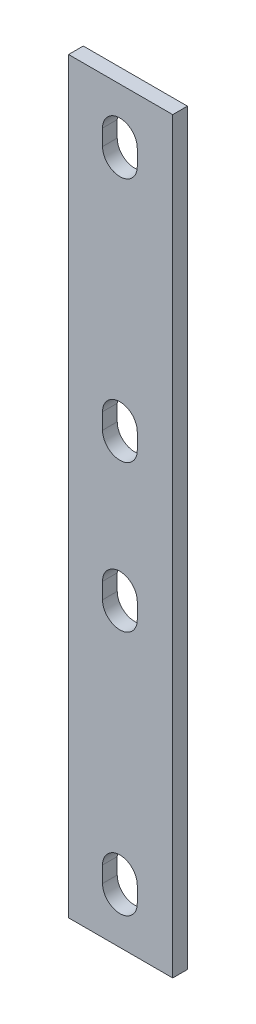
SolidWorks part; units mm, degrees
ref_plane "Front Plane" through (0, 0, 0) normal (0, 0, 1) x (1, 0, 0)
ref_plane "Top Plane" through (0, 0, 0) normal (0, 1, 0) x (1, 0, 0)
ref_plane "Right Plane" through (0, 0, 0) normal (1, 0, 0) x (0, 0, -1)
sketch "Sketch1" plane through (0, 0, 0) normal (0, 0, 1) x (1, 0, 0)
  line L1 (0, 0) -> (39, 0)
  line L2 (0, 0) -> (0, -280)
  line L3 (0, -280) -> (39, -280)
  line L4 (39, 0) -> (39, -280)
  dimension "D1" = 280
  dimension "D2" = 39
extrude "Boss-Extrude1" add sketch "Sketch1" along normal blind 5.5
sketch "Sketch4" plane through (0, 0, 5.5) normal (0, 0, 1) x (1, 0, 0)
  line L0 (0, -140) -> (21.8594, -140) construction
  line L5 (0, 0) -> (0, -280) construction
  line L6 (19.2173, -170.5) -> (19.2173, -164.5) construction
  line L7 (25.7173, -170.5) -> (25.7173, -164.5)
  line L8 (19.2173, -109.5) -> (19.2173, -115.5) construction
  line L9 (25.7173, -109.5) -> (25.7173, -115.5)
  line L10 (12.7173, -109.5) -> (12.7173, -115.5)
  line L11 (19.2173, -23.5) -> (19.2173, -17.5) construction
  line L12 (25.7173, -23.5) -> (25.7173, -17.5)
  line L13 (12.7173, -23.5) -> (12.7173, -17.5)
  line L14 (12.7173, -170.5) -> (12.7173, -164.5)
  line L15 (19.2173, -256.5) -> (19.2173, -262.5) construction
  line L16 (25.7173, -256.5) -> (25.7173, -262.5)
  line L17 (12.7173, -256.5) -> (12.7173, -262.5)
  arc A0 (25.7173, -109.5) -> (12.7173, -109.5) centre (19.2173, -109.5) ccw
  arc A1 (12.7173, -115.5) -> (25.7173, -115.5) centre (19.2173, -115.5) ccw
  arc A2 (25.7173, -23.5) -> (12.7173, -23.5) centre (19.2173, -23.5) cw
  arc A3 (12.7173, -17.5) -> (25.7173, -17.5) centre (19.2173, -17.5) cw
  arc A4 (25.7173, -170.5) -> (12.7173, -170.5) centre (19.2173, -170.5) cw
  arc A5 (12.7173, -164.5) -> (25.7173, -164.5) centre (19.2173, -164.5) cw
  arc A6 (25.7173, -256.5) -> (12.7173, -256.5) centre (19.2173, -256.5) ccw
  arc A7 (12.7173, -262.5) -> (25.7173, -262.5) centre (19.2173, -262.5) ccw
  point P6 (19.2173, -167.5)
  point P14 (19.2173, -112.5)
  point P21 (19.2173, -20.5)
  point P27 (19.2173, -259.5)
  dimension "D4" = 6.5
  dimension "D3" = 6
  dimension "D5" = 92
extrude "Cut-Extrude2" cut sketch "Sketch4" against normal blind 6
